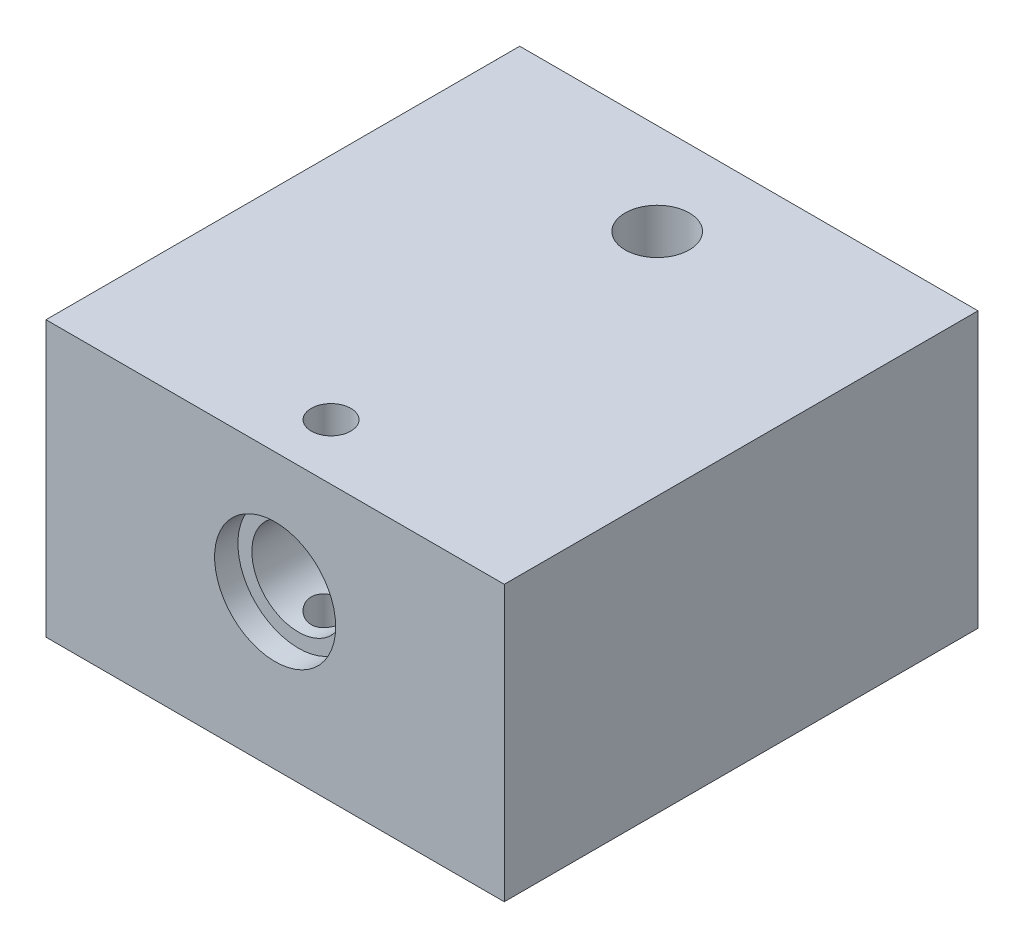
SolidWorks part; units mm, degrees
ref_plane "Front Plane" through (0, 0, 0) normal (0, 0, 1) x (1, 0, 0)
ref_plane "Top Plane" through (0, 0, 0) normal (0, 1, 0) x (1, 0, 0)
ref_plane "Right Plane" through (0, 0, 0) normal (1, 0, 0) x (0, 0, -1)
sketch "Sketch1" plane through (0, 0, 0) normal (0, 1, 0) x (1, 0, 0)
  line L1 (-82.7377, 56.7766) -> (-57.7377, 56.7766)
  line L2 (-82.7377, 56.7766) -> (-82.7377, 50.9346)
  line L3 (-82.7377, 50.9346) -> (-57.7377, 50.9346)
  line L4 (-57.7377, 56.7766) -> (-57.7377, 50.9346)
  dimension "D1" = 25
  dimension "D2" = 5.842
extrude "Boss-Extrude1" add sketch "Sketch1" along normal blind 15
sketch "Sketch5" plane through (0, 0, -50.9346) normal (0, 0, 1) x (1, 0, 0)
  line L0 (-82.7377, 15) -> (-57.7377, 15) construction
  line L1 (-82.7377, 8.396) -> (-70.2377, 8.396) construction
  line L2 (-82.7377, 15) -> (-82.7377, 0) construction
  line L3 (-70.2377, 8.396) -> (-57.7377, 8.396) construction
  line L4 (-57.7377, 15) -> (-57.7377, 0) construction
  circle A0 centre (-70.2377, 8.396) radius 2.54
  dimension "D1" = 6.604
  dimension "D2" = 5.08
extrude "Cut-Extrude3" cut sketch "Sketch5" against normal through all
sketch "Sketch7" plane through (0, 0, -50.9346) normal (0, 0, 1) x (1, 0, 0)
  circle A0 centre (-70.2377, 8.396) radius 3.302
  circle A1 centre (-70.2377, 8.396) radius 2.54 construction
  dimension "D1" = 6.604
extrude "Cut-Extrude4" cut sketch "Sketch7" against normal blind 1.27
sketch "Sketch10" plane through (0, 15, 0) normal (0, 1, 0) x (1, 0, 0)
  line L0 (-82.7377, 50.9346) -> (-57.7377, 50.9346) construction
  line L1 (-70.2377, 53.9826) -> (-82.7377, 53.9826) construction
  line L3 (-70.2377, 53.9826) -> (-57.7377, 53.9826) construction
  line L4 (-57.7377, 50.9346) -> (-57.7377, 56.7766) construction
  line L5 (-82.7377, 56.7766) -> (-82.7377, 50.9346) construction
  circle A0 centre (-70.2377, 53.9826) radius 1.0795
  dimension "D1" = 2.159
  dimension "D2" = 3.048
extrude "Cut-Extrude7" cut sketch "Sketch10" against normal through all
sketch "Sketch11" plane through (0, 0, -56.7766) normal (0, 0, -1) x (-1, 0, 0)
  line L1 (57.7377, 0) -> (82.7377, 0)
  line L2 (57.7377, 0) -> (57.7377, 15)
  line L3 (57.7377, 15) -> (82.7377, 15)
  line L4 (82.7377, 0) -> (82.7377, 15)
extrude "Boss-Extrude2" add sketch "Sketch11" along normal blind 20
sketch "Sketch12" plane through (0, 15, 0) normal (0, 1, 0) x (1, 0, 0)
  line L0 (-70.2377, 76.7766) -> (-70.2377, 50.9346) construction
  line L1 (-82.7377, 76.7766) -> (-57.7377, 76.7766) construction
  line L4 (-82.7377, 50.9346) -> (-57.7377, 50.9346) construction
  circle A0 centre (-70.2377, 71.7766) radius 1.75
  dimension "D1" = 3.5
  dimension "D2" = 5
extrude "Cut-Extrude8" cut sketch "Sketch12" against normal through all
